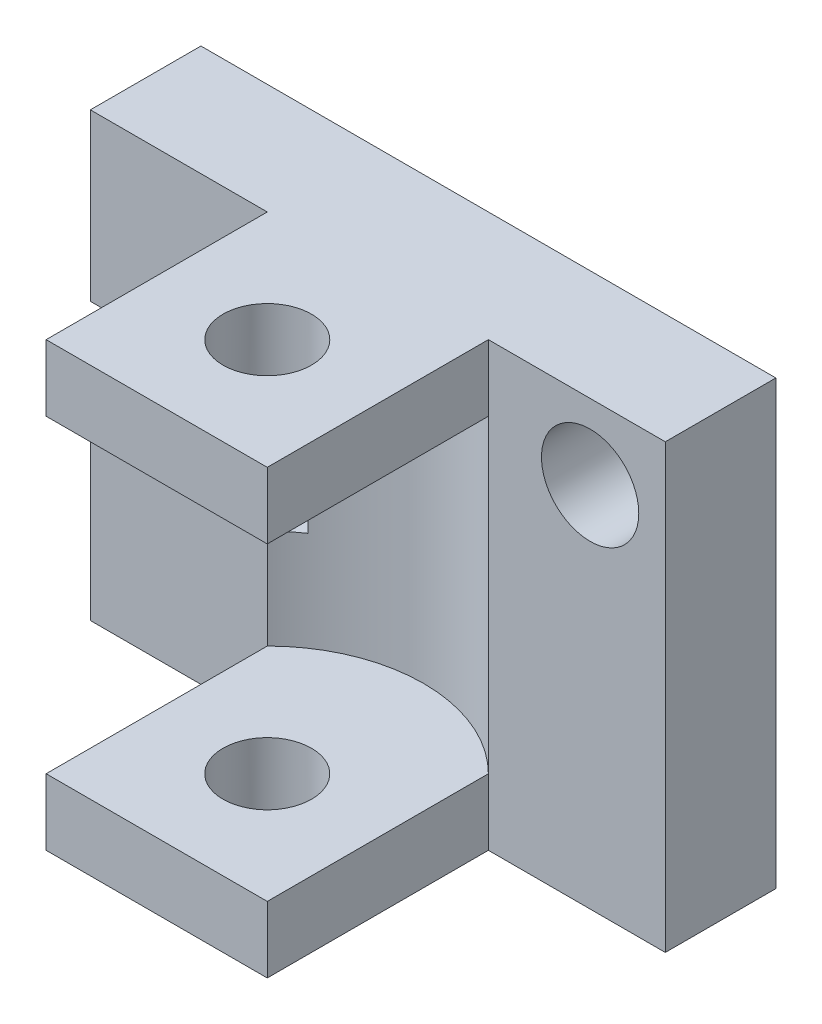
SolidWorks part; units mm, degrees
ref_plane "Спереди" through (0, 0, 0) normal (0, 0, 1) x (1, 0, 0)
ref_plane "Сверху" through (0, 0, 0) normal (0, 1, 0) x (1, 0, 0)
ref_plane "Справа" through (0, 0, 0) normal (1, 0, 0) x (0, 0, -1)
sketch "Эскиз1" plane through (0, 0, 0) normal (0, 0, 1) x (1, 0, 0)
  line L1 (-65, -50) -> (65, -50)
  line L2 (-65, -50) -> (-65, 50)
  line L3 (-65, 50) -> (65, 50)
  line L4 (65, -50) -> (65, 50)
  line L5 (-65, -50) -> (65, 50) construction
  line L6 (-65, 50) -> (65, -50) construction
  point P0 (0, 0)
  dimension "D1" = 100
  dimension "D2" = 130
extrude "Бобышка-Вытянуть1" add sketch "Эскиз1" along normal blind 25
sketch "Эскиз2" plane through (0, 50, 0) normal (0, 1, 0) x (1, 0, 0)
  line L0 (65, -25) -> (-65, -25) construction
  line L1 (25, -75) -> (-25, -75)
  line L2 (25, -75) -> (25, -25)
  line L3 (25, -25) -> (-25, -25)
  line L4 (-25, -75) -> (-25, -25)
  line L5 (25, -75) -> (-25, -25) construction
  line L6 (25, -25) -> (-25, -75) construction
  circle A0 centre (0, -50) radius 10
  point P0 (0, -50)
  dimension "D3" = 20
  dimension "D1" = 50
  dimension "D2" = 50
extrude "Бобышка-Вытянуть2" add sketch "Эскиз2" against normal up to surface (100 mm away) up to face at (0, -50, 12.5)
sketch "Эскиз3" plane through (0, 0, 25) normal (0, 0, 1) x (1, 0, 0)
  line L0 (65, 50) -> (25, 50) construction
  line L1 (65, -50) -> (65, 50) construction
  circle A0 centre (48, 33) radius 11
  dimension "D1" = 17
  dimension "D2" = 17
  dimension "D3" = 22
extrude "Вырез-Вытянуть1" cut sketch "Эскиз3" against normal through all
ref_plane "Плоскость1" through (0, 0, 0) normal (0, -1, 0) x (-1, 0, 0)
sketch "Эскиз4" plane through (0, 0, 0) normal (0, -1, 0) x (-1, 0, 0)
  circle A0 centre (0, -50) radius 35.3553
extrude "Вырез-Вытянуть2" cut sketch "Эскиз4" against normal mid plane 70
sketch "Эскиз5" plane through (0, 0, 25) normal (0, 0, 1) x (1, 0, 0)
  line L0 (-65, 0) -> (65, 0) construction
  line L1 (-65, 50) -> (-65, -50) construction
  line L2 (65, -50) -> (65, 50) construction
  line L4 (-20, -12.5) -> (-65, -12.5)
  line L5 (-20, -12.5) -> (-20, 12.5)
  line L6 (-20, 12.5) -> (-65, 12.5)
  line L7 (-65, -12.5) -> (-65, 12.5)
  line L8 (-20, -12.5) -> (-65, 12.5) construction
  line L9 (-20, 12.5) -> (-65, -12.5) construction
  point P6 (-42.5, 0)
  dimension "D1" = 45
  dimension "D2" = 25
extrude "Вырез-Вытянуть3" cut sketch "Эскиз5" against normal blind 15
